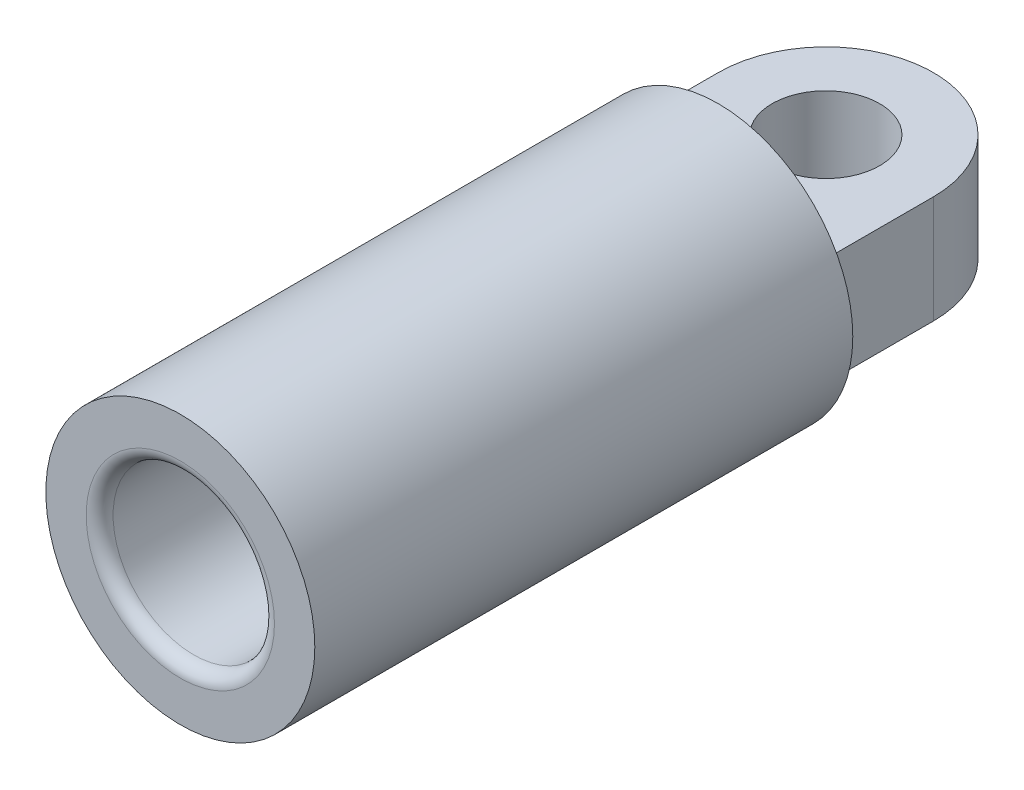
SolidWorks part; units mm, degrees
ref_plane "정면" through (0, 0, 0) normal (0, 0, 1) x (1, 0, 0)
ref_plane "윗면" through (0, 0, 0) normal (0, 1, 0) x (1, 0, 0)
ref_plane "우측면" through (0, 0, 0) normal (1, 0, 0) x (0, 0, -1)
sketch "스케치1" plane through (0, 0, 0) normal (0, 0, 1) x (1, 0, 0)
  circle A0 centre (0, 0) radius 25
  dimension "D1" = 50
extrude "보스-돌출1" add sketch "스케치1" against normal blind 30
sketch "스케치2" plane through (0, 0, -30) normal (0, 0, -1) x (-1, 0, 0)
  circle A1 centre (0, 0) radius 25
  dimension "D1" = 50
extrude "보스-돌출2" add sketch "스케치2" along normal blind 250
sketch "스케치3" plane through (0, 0, -280) normal (0, 0, -1) x (-1, 0, 0)
  line L0 (35, 0) -> (-35, 0)
  line L2 (-20, 10) -> (20, 10)
  line L3 (-20, 10) -> (-20, -10)
  line L4 (-20, -10) -> (20, -10)
  line L5 (20, 10) -> (20, -10)
  line L6 (-20, 10) -> (20, -10) construction
  line L7 (-20, -10) -> (20, 10) construction
  circle A0 centre (0, 0) radius 35
  dimension "D1" = 70
  dimension "D2" = 20
  dimension "D3" = 40
extrude "보스-돌출4" add sketch "스케치3" along normal blind 40 contours L5 L0 L3 L4 | L5 L2 L3 L0
sketch "스케치6" plane through (0, 10, 0) normal (0, 1, 0) x (1, 0, 0)
  line L0 (0, 320) -> (0, 280)
  line L1 (20, 320) -> (-20, 320) construction
  line L2 (20, 280) -> (-20, 280) construction
  circle A0 centre (0, 300) radius 20
  line M2 (20, 280) -> (20, 320)
  line M3 (20, 320) -> (-20, 320)
  line M4 (-20, 320) -> (-20, 280)
extrude "컷-돌출1" cut sketch "스케치6" against normal through all both and the other way through all contours A0 M3 M4 | A0 M2 M3
sketch "스케치7" plane through (0, 10, 0) normal (0, 1, 0) x (1, 0, 0)
  circle A0 centre (0, 300) radius 10
  dimension "D1" = 20
extrude "컷-돌출2" cut sketch "스케치7" against normal through all both and the other way through all
sketch "스케치8" plane through (0, 0, 0) normal (0, 0, 1) x (1, 0, 0)
  circle A0 centre (0, 0) radius 25
extrude "컷-돌출3" cut sketch "스케치8" against normal blind 180
sketch "스케치9" plane through (0, 0, -180) normal (0, 0, 1) x (1, 0, 0)
  circle A0 centre (0, 0) radius 15
  dimension "D1" = 30
extrude "컷-돌출4" cut sketch "스케치9" against normal blind 30
fillet "필렛1" radius 2.5 1 edges at (15, 0, -180)
